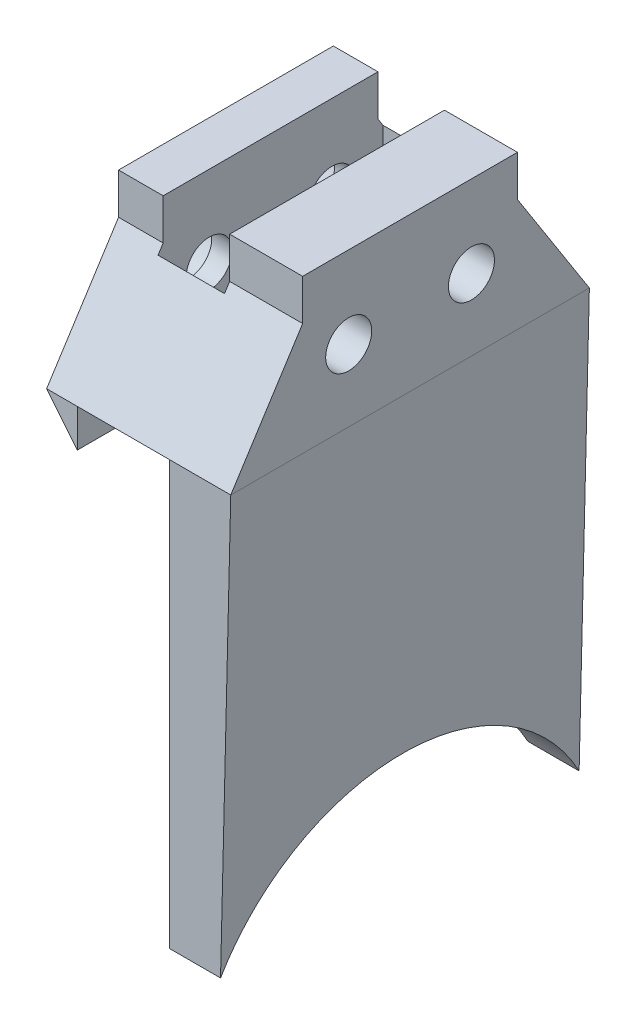
SolidWorks part; units mm, degrees
ref_plane "Front Plane" through (0, 0, 0) normal (0, 0, 1) x (1, 0, 0)
ref_plane "Top Plane" through (0, 0, 0) normal (0, 1, 0) x (1, 0, 0)
ref_plane "Right Plane" through (0, 0, 0) normal (1, 0, 0) x (0, 0, -1)
sketch "Gripper Attachment Base Sketch" plane through (0, 0, 0) normal (0, 0, 1) x (1, 0, 0)
  line L5 (6, 7.5) -> (-6, 7.5)
  line L6 (6, 7.5) -> (6, -7.5)
  line L7 (6, -7.5) -> (-6, -7.5)
  line L8 (-6, 7.5) -> (-6, -7.5)
  line L9 (6, 7.5) -> (-6, -7.5) construction
  line L10 (6, -7.5) -> (-6, 7.5) construction
  point P0 (0, 0)
  dimension "D1" = 12
  dimension "D2" = 15
extrude "Gripper Attachment Base" add sketch "Gripper Attachment Base Sketch" along normal blind 35.0589
sketch "Thickener Base Sketch" plane through (6, 0, 0) normal (1, 0, 0) x (0, 0, -1)
  line L0 (-35.0589, -7.5) -> (-35.0589, 7.5) construction
  line L1 (0, 7.5) -> (-35.0589, 7.5)
  line L2 (0, 7.5) -> (0, -48.8959)
  line L4 (-35.0589, 7.5) -> (-35.0589, -48.8959)
  line L5 (0, -7.5) -> (-35.0589, -7.5) construction
  arc A0 (0, -48.8959) -> (-35.0589, -48.8959) centre (-17.5294, -58.525) ccw
  dimension "D1" = 40
  dimension "D2" = 41.3959
extrude "Thickener Base" add sketch "Thickener Base Sketch" along normal blind 6
sketch "Define Thickness Plane 1" plane through (0, 0, 0) normal (0, 0, 1) x (1, 0, 0)
  line L0 (11, -48.8959) -> (12, -7.5) construction
  line L1 (12, -48.8959) -> (6, -48.8959) construction
  line L2 (12, -48.8959) -> (12, 7.5) construction
  dimension "D1" = 5
sketch "Define Thickness Plane 2" plane through (0, 0, 35.0589) normal (0, 0, 1) x (1, 0, 0)
  line L0 (11, -48.8959) -> (12, -7.5) construction
  line L1 (12, 7.5) -> (12, -48.8959) construction
ref_plane "Thickness Plane" through (12.1741, -0.2941, 0) normal (0.9997, -0.0241, 0) x (0, 0, -1)
sketch "Thickness Cutoff Sketch" plane through (12.1741, -0.2941, 0) normal (0.9997, -0.0241, 0) x (0, 0, -1)
  line L0 (0, 7.7876) -> (-35.0589, 7.7876) construction
  line L1 (-45.0589, 17.7876) -> (10, 17.7876)
  line L2 (-45.0589, 17.7876) -> (-45.0589, -58.5919)
  line L3 (-45.0589, -58.5919) -> (10, -58.5919)
  line L4 (10, 17.7876) -> (10, -58.5919)
  line L5 (-35.0589, 7.7876) -> (-35.0589, -48.5919) construction
  line L6 (0, -48.5919) -> (0, 7.7876) construction
  dimension "D1" = 10
  dimension "D2" = 10
  dimension "D3" = 10
  dimension "D4" = 10
extrude "Thickness Cutoff" cut sketch "Thickness Cutoff Sketch" along normal through all
sketch "Excess Material Cutoff Sketch" plane through (0, -520.6815, 0) normal (1, 0, 0) x (0, 0, 1)
  line L3 (7.0294, -528.1815) -> (0, -528.1815)
  line L4 (0, -528.1815) -> (0, -513.1815)
  line L5 (28.0294, -528.1815) -> (35.0589, -528.1815)
  line L6 (35.0589, -528.1815) -> (35.0589, -513.1815)
  line L7 (7.0294, -528.1815) -> (7.0294, -524.1815)
  line L8 (7.0294, -524.1815) -> (0, -513.1815)
  line L9 (28.0294, -528.1815) -> (28.0294, -524.1815)
  line L10 (28.0294, -524.1815) -> (35.0589, -513.1815)
  line L11 (0, -513.1815) -> (0, -471.7856) construction
  line L15 (0, -528.1815) -> (35.0589, -528.1815) construction
  dimension "D1" = 21
  dimension "D2" = 21
  dimension "D3" = 4
extrude "Excess Material Cutoff" cut sketch "Excess Material Cutoff Sketch" along normal through all and the other way through all
sketch "Finger Cavity Cutout Sketch" plane through (0, 7.5, 0) normal (0, 1, 0) x (1, 0, 0)
  line L0 (12, -7.0294) -> (12, -28.0294) construction
  line L1 (-1.6375, -6.5294) -> (4.8625, -6.5294)
  line L2 (-1.6375, -6.5294) -> (-1.6375, -28.5294)
  line L3 (-1.6375, -28.5294) -> (4.8625, -28.5294)
  line L4 (4.8625, -6.5294) -> (4.8625, -28.5294)
  line L5 (-1.6375, -17.5294) -> (12, -17.5294) construction
  point P12 (-1.6375, -17.5294)
  point P15 (1.6125, -6.5294)
  dimension "D1" = 10.3875
  dimension "D2" = 22
  dimension "D3" = 6.5
extrude "Finger Cavity Cutout" cut sketch "Finger Cavity Cutout Sketch" against normal blind 15
sketch "Screw Through-Holes Sketch" plane through (-6, 0, 0) normal (-1, 0, 0) x (0, 0, 1)
  line L0 (28.0294, 7.5) -> (7.0294, 7.5) construction
  line L1 (11.5294, -0.5) -> (23.5294, -0.5) construction
  line L2 (17.5294, -0.5) -> (17.5294, 7.5) construction
  circle A0 centre (11.5294, -0.5) radius 2.25
  circle A1 centre (23.5294, -0.5) radius 2.25
  dimension "D1" = 4.5
  dimension "D2" = 4.5
  dimension "D3" = 12
  dimension "D4" = 8
extrude "Screw Through-Holes" cut sketch "Screw Through-Holes Sketch" against normal through all
sketch "Socket Recesses Sketch" plane through (-6, 0, 0) normal (-1, 0, 0) x (0, 0, 1)
  circle A0 centre (11.5294, -0.5) radius 3.75
  circle A1 centre (23.5294, -0.5) radius 3.75
  circle A2 centre (11.5294, -0.5) radius 2.25 construction
  dimension "D1" = 7.5
  dimension "D2" = 7.5
extrude "Socket Recesses" cut sketch "Socket Recesses Sketch" against normal blind 2.3625
sketch "Shaping to Electronics Plate Sketch" plane through (0, 0, 0) normal (0, 0, 1) x (1, 0, 0)
  line L0 (-6, -7.5) -> (-3, -11.2)
  line L1 (-3, -11.2) -> (-3, -7.5)
  line L2 (-6, -7.5) -> (6, -7.5) construction
  line L3 (-3, -7.5) -> (-6, -7.5)
  dimension "D1" = 3.7
  dimension "D2" = 3
extrude "Shaping to Electronics Plate" add sketch "Shaping to Electronics Plate Sketch" along normal through all
